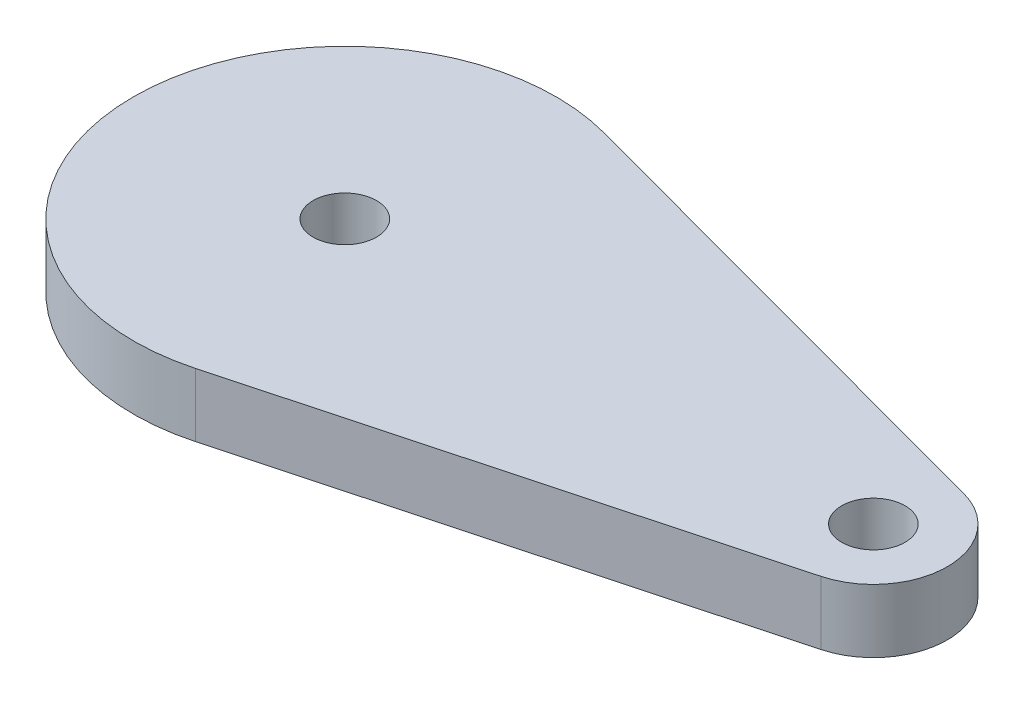
SolidWorks part; units mm, degrees
ref_plane "Front Plane" through (0, 0, 0) normal (0, 0, 1) x (1, 0, 0)
ref_plane "Top Plane" through (0, 0, 0) normal (0, 1, 0) x (1, 0, 0)
ref_plane "Right Plane" through (0, 0, 0) normal (1, 0, 0) x (0, 0, -1)
sketch "Sketch2" plane through (0, 0, 0) normal (0, 1, 0) x (1, 0, 0)
  line L0 (0, -12.5) -> (0, 12.5)
  line L1 (0, -12.5) -> (-25, -12.5)
  line L2 (0, 12.5) -> (25, 12.5)
  line L3 (0, 0) -> (-12.4066, 38.0273)
  line L4 (-12.4066, 38.0273) -> (-32, 22.5)
  line L5 (-32, 22.5) -> (-52.7065, 30.7)
  line L6 (-52.7065, 30.7) -> (-30.6151, 86.485)
  line L7 (-12, 27.5) -> (-10.6151, 91.485)
  line L8 (-32, 22.5) -> (-30.6151, 86.485) construction
  line L9 (-10.6151, 91.485) -> (-30.6151, 86.485)
  line L10 (0, -75.8918) -> (0, 75.8918) construction
  line L11 (0, 0) -> (12.4066, 38.0273)
  line L12 (32, 22.5) -> (30.6151, 86.485) construction
  line L13 (10.6151, 91.485) -> (30.6151, 86.485)
  line L14 (12, 27.5) -> (10.6151, 91.485)
  line L15 (52.7065, 30.7) -> (30.6151, 86.485)
  line L16 (32, 22.5) -> (52.7065, 30.7)
  line L17 (12.4066, 38.0273) -> (32, 22.5)
  line L18 (-25, -6.5) -> (-25, -46.5) construction
  line L19 (-15, -6.5) -> (-35, -6.5)
  line L20 (-15, -6.5) -> (-15, -46.5)
  line L21 (-15, -46.5) -> (-35, -46.5)
  line L22 (-35, -6.5) -> (-35, -46.5)
  circle A0 centre (25, 12.5) radius 1.5
  circle A1 centre (-25, -12.5) radius 1.5
  circle A2 centre (-12, 27.5) radius 1.5
  circle A3 centre (-32, 22.5) radius 1.5
  circle A4 centre (32, 22.5) radius 1.5
  circle A5 centre (12, 27.5) radius 1.5
  circle A6 centre (-25, -12.5) radius 10
  point P15 (0, 0)
  dimension "D3" = 3
  dimension "D20" = 20
  dimension "D1" = 25
  dimension "D2" = 25
  dimension "D5" = 12.5
  dimension "D4" = 12.5
  dimension "D6" = 25
  dimension "D7" = 25
  dimension "D8" = 40
  dimension "D10" = 25
  dimension "D11" = 120
  dimension "D15" = 20
  dimension "D17" = 40
  dimension "D9" = 12
  dimension "D14" = 5
  dimension "D13" = 64
  dimension "D12" = 60
  dimension "D16" = 40
  dimension "D18" = 20
  dimension "D19" = 6
sketch "Sketch3" plane through (0, 0, 0) normal (0, 1, 0) x (1, 0, 0)
  line L0 (-22.4, -2.8439) -> (0.91, -9.1204)
  line L1 (0.91, -15.8796) -> (-22.4, -22.1561)
  circle A0 centre (0, -12.5) radius 1.5
  circle A1 centre (-25, -12.5) radius 10 construction
  arc A2 (-22.4, -2.8439) -> (-22.4, -22.1561) centre (-25, -12.5) ccw
  arc A3 (0.91, -15.8796) -> (0.91, -9.1204) centre (0, -12.5) ccw
  circle A5 centre (0, -12.5) radius 3.5 construction
  circle A6 centre (-25, -12.5) radius 1.5 construction
  circle A7 centre (-25, -12.5) radius 1.5
  dimension "D1" = 3
  dimension "D2" = 2
extrude "Boss-Extrude1" add sketch "Sketch3" along normal blind 3
equation "\"a\"= \"b\" / 2"
equation "\"b\"= 25"
equation "\"D1@Sketch2\"=2*\"a\""
equation "\"D2@Sketch2\"=\"b\""
equation "\"D5@Sketch2\"=\"a\""
equation "\"D4@Sketch2\"=\"a\""
equation "\"D6@Sketch2\"=\"b\""
equation "\"D7@Sketch2\"=\"b\""
equation "\"c\"= 64"
equation "\"D13@Sketch2\"=\"c\""
equation "\"D12@Sketch2\"=\"c\"-4"
